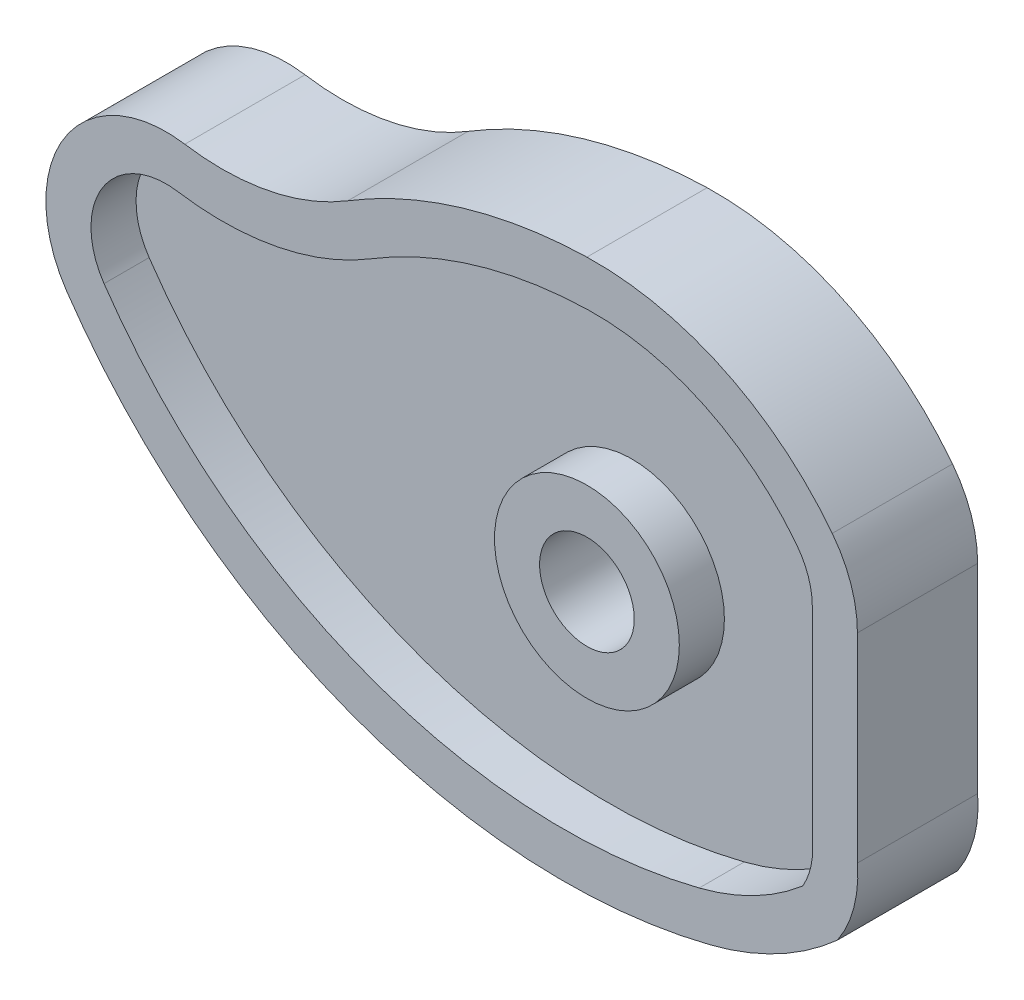
SolidWorks part; units mm, degrees
ref_plane "Front Plane" through (0, 0, 0) normal (0, 0, 1) x (1, 0, 0)
ref_plane "Top Plane" through (0, 0, 0) normal (0, 1, 0) x (1, 0, 0)
ref_plane "Right Plane" through (0, 0, 0) normal (1, 0, 0) x (0, 0, -1)
sketch "Sketch1" plane through (0, 0, 0) normal (0, 0, 1) x (1, 0, 0)
  line L0 (0, 106.3447) -> (0, -73.4214) construction
  line L1 (-250.4001, 0) -> (114.3, 0) construction
  line L3 (69.3, 51.8719) -> (69.3, -31.9587) construction
  line L4 (114.3, 42.12) -> (114.3, -42.12)
  arc A1 (114.3, 42.12) -> (103.6785, 73.2058) centre (63.5, 42.12) ccw
  arc A2 (103.6785, 73.2058) -> (0, 122.4502) centre (3.2322, -4.5086) ccw
  arc A3 (0, 122.4502) -> (-101.0236, 92.5582) centre (5.1715, -80.684) ccw
  arc A4 (-101.0236, 92.5582) -> (-169.9071, 78.8131) centre (-154.1212, 179.1792) cw
  arc A5 (-169.9071, 78.8131) -> (-219.7638, 0) centre (-177.8, 28.63) ccw
  arc A6 (-219.7638, 0) -> (52.0953, -103.1568) centre (-9.9447, 143.15) ccw
  arc A7 (114.3, -42.12) -> (105.83, -74.5848) centre (63.668, -46.2475) cw
  arc A8 (52.0953, -103.1568) -> (105.83, -74.5848) centre (21.0753, 19.9966) ccw
  circle A9 centre (0, 0) radius 20
  dimension "D6" = 50.8
  dimension "D8" = 50.8
  dimension "D9" = 127
  dimension "D10" = 203.2
  dimension "D11" = 101.6
  dimension "D12" = 50.8
  dimension "D13" = 254
  dimension "D7" = 127
  dimension "D16" = 40
  dimension "D1" = 45
  dimension "D2" = 84.24
  dimension "D3" = 42.12
  dimension "D4" = 114.3
  dimension "D5" = 105.83
  dimension "D14" = 28.63
  dimension "D15" = 177.8
extrude "Boss-Extrude1" add sketch "Sketch1" along normal blind 50.8
sketch "Sketch2" plane through (0, 0, 50.8) normal (0, 0, 1) x (1, 0, 0)
  line L0 (114.3, -42.12) -> (114.3, 42.12) construction
  line L1 (114.3, -42.12) -> (114.3, 42.12)
  line L2 (95.25, -42.986) -> (95.25, 42.12)
  arc A0 (114.3, 42.12) -> (103.6785, 73.2058) centre (63.5, 42.12) ccw construction
  arc A1 (105.83, -74.5848) -> (114.3, -42.12) centre (63.668, -46.2475) ccw construction
  arc A2 (52.0953, -103.1568) -> (105.83, -74.5848) centre (21.0753, 19.9966) ccw construction
  arc A3 (-219.7638, 0) -> (52.0953, -103.1568) centre (-9.9447, 143.15) ccw construction
  arc A4 (-169.9071, 78.8131) -> (-219.7638, 0) centre (-177.8, 28.63) ccw construction
  arc A5 (-169.9071, 78.8131) -> (-101.0236, 92.5582) centre (-154.1212, 179.1792) ccw construction
  arc A6 (0, 122.4502) -> (-101.0236, 92.5582) centre (5.1715, -80.684) ccw construction
  arc A7 (103.6785, 73.2058) -> (0, 122.4502) centre (3.2322, -4.5086) ccw construction
  arc A8 (114.3, 42.12) -> (103.6785, 73.2058) centre (63.5, 42.12) ccw
  arc A9 (105.83, -74.5848) -> (114.3, -42.12) centre (63.668, -46.2475) ccw
  arc A10 (52.0953, -103.1568) -> (105.83, -74.5848) centre (21.0753, 19.9966) ccw
  arc A11 (-219.7638, 0) -> (52.0953, -103.1568) centre (-9.9447, 143.15) ccw
  arc A12 (-169.9071, 78.8131) -> (-219.7638, 0) centre (-177.8, 28.63) ccw
  arc A13 (-169.9071, 78.8131) -> (-101.0236, 92.5582) centre (-154.1212, 179.1792) ccw
  arc A14 (0, 122.4502) -> (-101.0236, 92.5582) centre (5.1715, -80.684) ccw
  arc A15 (103.6785, 73.2058) -> (0, 122.4502) centre (3.2322, -4.5086) ccw
  arc A16 (0.4848, 103.4064) -> (-91.0678, 76.3167) centre (5.1715, -80.684) ccw
  arc A17 (-172.8669, 59.9944) -> (-91.0678, 76.3167) centre (-154.1212, 179.1792) ccw
  arc A18 (-172.8669, 59.9944) -> (-204.0274, 10.7363) centre (-177.8, 28.63) ccw
  arc A19 (-204.0274, 10.7363) -> (47.4423, -84.6838) centre (-9.9447, 143.15) ccw
  arc A20 (47.4423, -84.6838) -> (91.1837, -62.0888) centre (21.0753, 19.9966) ccw
  arc A21 (91.1837, -62.0888) -> (95.25, -42.986) centre (63.668, -46.2475) ccw
  arc A22 (95.25, 42.12) -> (88.6116, 61.5486) centre (63.5, 42.12) ccw
  arc A23 (88.6116, 61.5486) -> (0.4848, 103.4064) centre (3.2322, -4.5086) ccw
  circle A24 centre (0, 0) radius 39.05
  point P37 (0, 0)
  point P38 (0, 0)
  point P39 (0, 0)
  dimension "D2" = 78.1
  dimension "D1" = 19.05
ref_plane "Plane1" through (0, 0, 25.4) normal (0, 0, 1) x (1, 0, 0)
extrude "Cut-Extrude2" cut sketch "Sketch2" against normal blind 19.05 contours A22 A23 A16 A17 A18 A19 A20 A21 L2 A24
ref_plane "Plane2" through (0, 0, 25.4) normal (0, 0, 1) x (1, 0, 0)
mirror "Mirror5" about plane through (0, 0, 25.4) normal (0, 0, 1) of "Cut-Extrude2"
